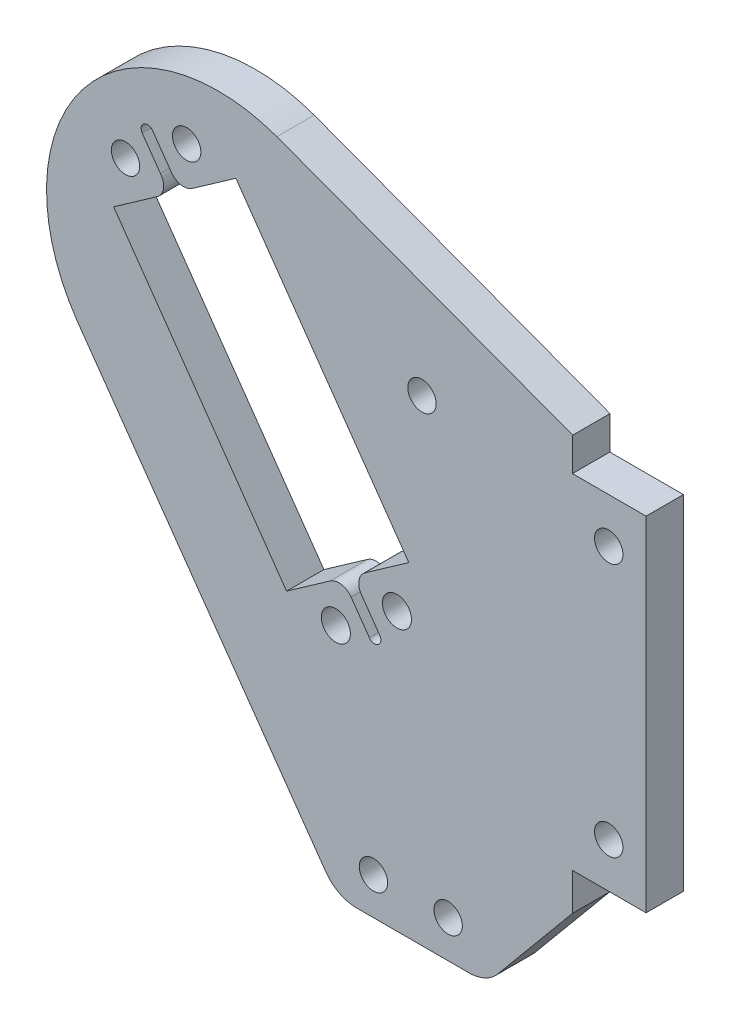
SolidWorks part; units mm, degrees
ref_plane "Plan de face" through (0, 0, 0) normal (0, 0, 1) x (1, 0, 0)
ref_plane "Plan de dessus" through (0, 0, 0) normal (0, 1, 0) x (1, 0, 0)
ref_plane "Plan de droite" through (0, 0, 0) normal (1, 0, 0) x (0, 0, -1)
sketch "Esquisse1" plane through (0, 0, 0) normal (0, 0, 1) x (1, 0, 0)
  line L0 (-14.8092, 33.7997) -> (-20.6609, 29.6912)
  line L1 (-31.1776, 22.3074) -> (-8.0206, -10.6751)
  line L2 (8.3478, 0.8172) -> (2.4961, -3.2913)
  line L3 (-14.8092, 33.7997) -> (8.3478, 0.8172)
  line L4 (-36.0421, 6.6123) -> (-2.7569, -40.6081)
  line L5 (30.2891, 26.5637) -> (-9.322, 41.3694)
  line L6 (30.2505, 22.0854) -> (30.2891, 26.5637)
  line L7 (40.1105, 22.0854) -> (30.2505, 22.0854)
  line L8 (40.1105, -23.9146) -> (40.1105, 22.0854)
  line L9 (30.2505, -23.9146) -> (40.1105, -23.9146)
  line L10 (30.2505, -28.9084) -> (30.2505, -23.9146)
  line L11 (20.2593, -40.9241) -> (30.2505, -28.9084)
  line L12 (1.3299, -42.7274) -> (16.4147, -42.7274)
  line L13 (-27.3577, 32.7831) -> (-24.9156, 29.3048)
  line L14 (-25.9249, 33.7099) -> (-23.4828, 30.2316)
  line L15 (0.6172, -7.0542) -> (3.0593, -10.5325)
  line L16 (2.0085, -6.0774) -> (4.4506, -9.5557)
  line L17 (-2.1689, -6.5666) -> (-8.0206, -10.6751)
  line L18 (-25.3259, 26.4159) -> (-31.1776, 22.3074)
  line L19 (40.1105, -0.9084) -> (-2.6592, -0.9084) construction
  line L20 (-35.12, 45.3254) -> (15.8698, -27.2993) construction
  arc A0 (-2.7569, -40.6081) -> (1.3299, -42.7274) centre (1.3299, -37.7274) ccw
  arc A1 (-9.322, 41.3694) -> (-36.0421, 6.6123) centre (-17.1611, 19.7465) ccw
  arc A2 (16.4147, -42.7274) -> (20.2593, -40.9241) centre (16.4147, -37.7274) ccw
  circle A3 centre (-29.5851, 28.7406) radius 1.9
  circle A4 centre (-21.4009, 34.4867) radius 1.9
  circle A5 centre (-1.4289, -11.3622) radius 1.95
  circle A6 centre (6.7553, -5.616) radius 1.95
  circle A7 centre (10.1041, 21.0535) radius 1.9
  circle A8 centre (3.6086, -37.7436) radius 1.9
  circle A9 centre (13.6086, -37.7309) radius 1.9
  circle A10 centre (35.1105, -17.9146) radius 1.9
  circle A11 centre (35.1105, 16.0852) radius 1.9
  arc A12 (-23.4828, 30.2316) -> (-20.6609, 29.6912) centre (-21.8101, 31.328) ccw
  arc A13 (-27.1316, 33.9448) -> (-27.3577, 32.7831) centre (-26.6413, 33.2465) ccw
  arc A14 (-25.9249, 33.7099) -> (-27.1316, 33.9448) centre (-26.6413, 33.2465) ccw
  arc A15 (3.0593, -10.5325) -> (4.2434, -10.7398) centre (3.755, -10.0441) ccw
  arc A16 (4.2434, -10.7398) -> (4.4506, -9.5557) centre (3.755, -10.0441) ccw
  arc A17 (2.4961, -3.2913) -> (2.0085, -6.0774) centre (3.6453, -4.9281) ccw
  arc A18 (0.6172, -7.0542) -> (-2.1689, -6.5666) centre (-1.0197, -8.2035) ccw
  arc A19 (-25.3259, 26.4159) -> (-24.9156, 29.3048) centre (-26.4751, 28.0527) ccw
  dimension "D3" = 3.8
  dimension "D4" = 5
  dimension "D9" = 5
  dimension "D13" = 6
  dimension "D1" = 46
  dimension "D2" = 9.86
  dimension "D5" = 9.86
  dimension "D6" = 20
  dimension "D7" = 40.3
  dimension "D8" = 5
  dimension "D10" = 54.927
  dimension "D11" = 10
  dimension "D12" = 110
extrude "Boss.-Extru.1" add sketch "Esquisse1" along normal blind 5
